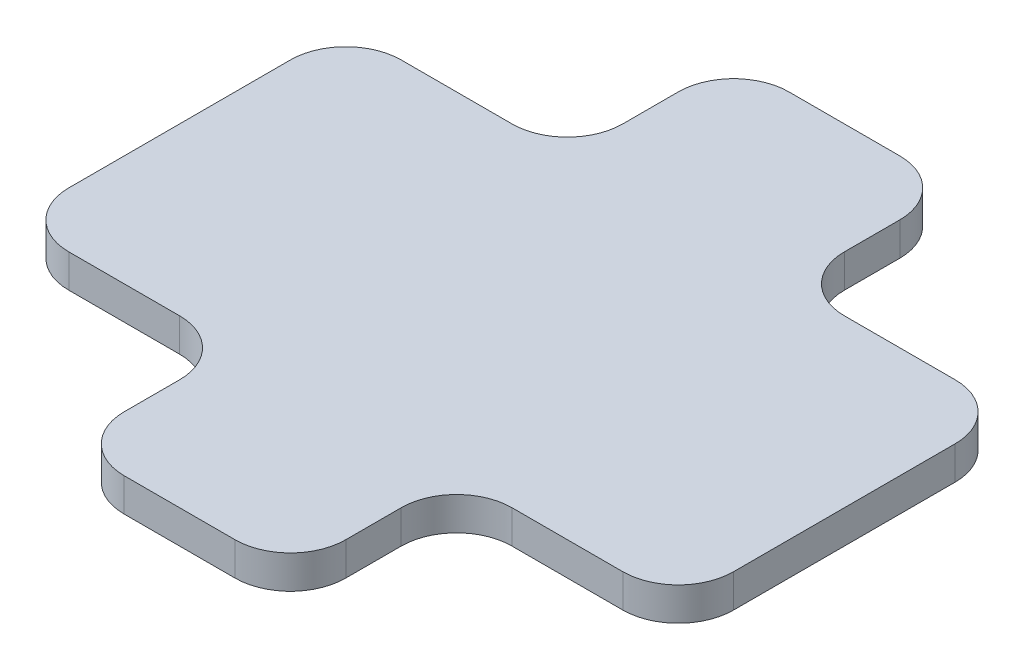
SolidWorks part; units mm, degrees
ref_plane "前视基准面" through (0, 0, 0) normal (0, 0, 1) x (1, 0, 0)
ref_plane "上视基准面" through (0, 0, 0) normal (0, 1, 0) x (1, 0, 0)
ref_plane "右视基准面" through (0, 0, 0) normal (1, 0, 0) x (0, 0, -1)
other "Configuration Table"
sketch "草图1" plane through (0, 0, 0) normal (0, 1, 0) x (1, 0, 0)
  line L0 (10, 15) -> (30, 15)
  line L1 (-10, 30) -> (10, 30)
  line L2 (-10, 30) -> (-10, 15)
  line L3 (-10, -30) -> (10, -30)
  line L4 (10, 30) -> (10, 15)
  line L5 (-10, 30) -> (10, -30) construction
  line L6 (-10, -30) -> (10, 30) construction
  line L7 (-30, 15) -> (-10, 15)
  line L8 (-30, 15) -> (-30, -15)
  line L9 (-30, -15) -> (-10, -15)
  line L10 (30, 15) -> (30, -15)
  line L11 (-30, 15) -> (30, -15) construction
  line L12 (-30, -15) -> (30, 15) construction
  line L13 (-10, -15) -> (-10, -30)
  line L14 (10, -15) -> (30, -15)
  line L15 (10, -15) -> (10, -30)
  point P0 (0, 0)
  point P6 (0, 0)
  dimension "D1" = 60
  dimension "D2" = 30
  dimension "D3" = 20
  dimension "D4" = 60
extrude "凸台-拉伸1" add sketch "草图1" along normal blind 3
fillet "圆角1" radius 5 12 edges at (-30, 1.5, 15) (-10, 1.5, 15) (-10, 1.5, 30) (10, 1.5, 30) (10, 1.5, 15) (30, 1.5, 15) (30, 1.5, -15) (-30, 1.5, -15) (-10, 1.5, -15) (10, 1.5, -15) (10, 1.5, -30) (-10, 1.5, -30)
